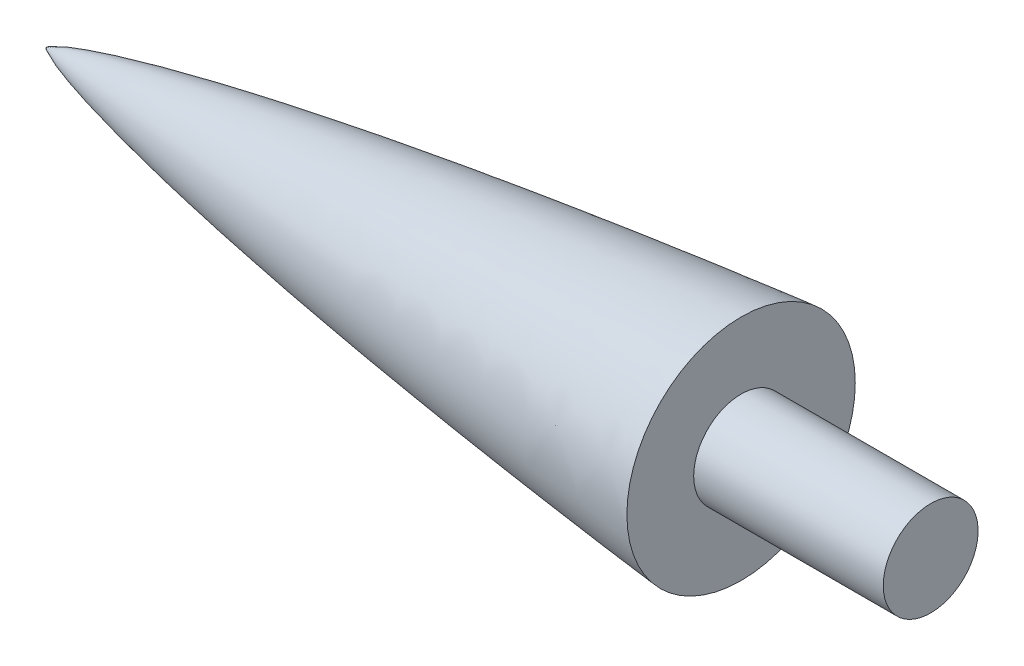
SolidWorks part; units mm, degrees
ref_plane "Front Plane" through (0, 0, 0) normal (0, 0, 1) x (1, 0, 0)
ref_plane "Top Plane" through (0, 0, 0) normal (0, 1, 0) x (1, 0, 0)
ref_plane "Right Plane" through (0, 0, 0) normal (1, 0, 0) x (0, 0, -1)
sketch "Sketch1" plane through (0, 0, 0) normal (0, 1, 0) x (1, 0, 0)
  line L0 (0, 0) -> (237, 0)
  line L1 (237, 0) -> (237, 12.7)
  line L2 (237, 12.7) -> (186.2, 12.7)
  line L3 (186.2, 12.7) -> (186.2, 30.5942)
  spline S0 degree 4 poles (0, 0) (0.0031, 0.0089) (0.0111, 0.0257) (0.0338, 0.0559) (0.0701, 0.0952) (0.1142, 0.1363) (0.1781, 0.1898) (0.2651, 0.2559) (0.3949, 0.3452) (0.607, 0.4767) (0.9521, 0.6686) (1.5402, 0.9598) (2.5741, 1.4116) (4.4139, 2.1149) (7.6024, 3.1739) (13.1065, 4.7592) (21.4404, 6.8338) (32.2223, 9.1851) (44.8484, 11.6455) (58.226, 14.0196) (69.9564, 15.9447) (80.0264, 17.506) (90.1038, 19.0036) (100.194, 20.4428) (110.2852, 21.8148) (120.3976, 23.1287) (128.8107, 24.1849) (134.7327, 24.9088) (139.7534, 25.5109) (144.8775, 26.1134) (149.8111, 26.687) (155.9483, 27.3807) (162.3431, 28.0928) (169.6409, 28.8782) (175.5202, 29.5034) (183.0749, 30.2794) (187.498, 30.7264) (193.3679, 31.3094) (197.7185, 31.7328) (201.3952, 32.0865) (203.6241, 32.2976) (204.8291, 32.4117) knots 0 0 0 0 0 0.00018 0.00036 0.00072 0.00103 0.001339 0.001964 0.002822 0.00406 0.00614 0.00956 0.015447 0.025766 0.044032 0.074197 0.125648 0.19101 0.256372 0.321734 0.387096 0.419777 0.452458 0.51782 0.583183 0.615864 0.648545 0.681226 0.697566 0.713907 0.746588 0.779269 0.81195 0.844631 0.877312 0.909993 0.932495 0.954996 0.977498 1 1 1 1 1 construction
  spline S1 degree 4 poles (0, 0) (0.0031, 0.0089) (0.0111, 0.0257) (0.0338, 0.0559) (0.0701, 0.0952) (0.1142, 0.1363) (0.1781, 0.1898) (0.2651, 0.2559) (0.3949, 0.3452) (0.607, 0.4767) (0.9521, 0.6686) (1.5402, 0.9598) (2.5741, 1.4116) (4.4139, 2.1149) (7.6024, 3.1739) (13.1065, 4.7592) (21.4404, 6.8338) (32.2223, 9.1851) (44.8484, 11.6455) (58.226, 14.0196) (69.9564, 15.9447) (80.0264, 17.506) (90.1038, 19.0036) (100.194, 20.4428) (110.2852, 21.8148) (120.3976, 23.1287) (128.8107, 24.1849) (134.7327, 24.9088) (139.7534, 25.5109) (144.8775, 26.1134) (149.8111, 26.687) (155.9483, 27.3807) (162.3431, 28.0928) (169.6409, 28.8782) (175.5202, 29.5034) (181.6647, 30.1346) (184.6624, 30.4393) (186.2, 30.5942) knots 0 0 0 0 0 0.00018 0.00036 0.00072 0.00103 0.001339 0.001964 0.002822 0.00406 0.00614 0.00956 0.015447 0.025766 0.044032 0.074197 0.125648 0.19101 0.256372 0.321734 0.387096 0.419777 0.452458 0.51782 0.583183 0.615864 0.648545 0.681226 0.697566 0.713907 0.746588 0.779269 0.81195 0.844631 0.877312 0.909993 0.909993 0.909993 0.909993 0.909993
revolve "Revolve1" add sketch "Sketch1" angle 360 about L0
